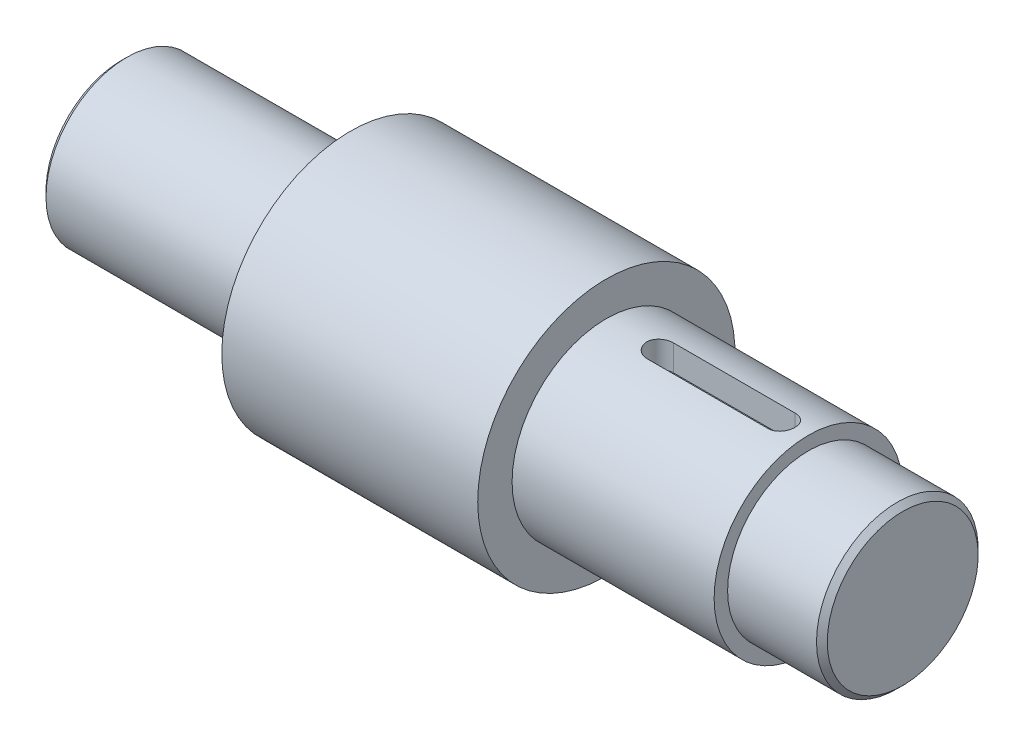
SolidWorks part; units mm, degrees
ref_plane "Alzado" through (0, 0, 0) normal (0, 0, 1) x (1, 0, 0)
ref_plane "Planta" through (0, 0, 0) normal (0, 1, 0) x (1, 0, 0)
ref_plane "Vista lateral" through (0, 0, 0) normal (1, 0, 0) x (0, 0, -1)
sketch "Croquis1" plane through (0, 0, 0) normal (0, 0, 1) x (1, 0, 0)
  line L0 (0, 0) -> (290, 0)
  line L1 (290, 0) -> (290, 30)
  line L2 (290, 30) -> (255, 30)
  line L5 (85, 47.75) -> (85, 30)
  line L6 (85, 30) -> (0, 30)
  line L7 (0, 30) -> (0, 0)
  line L8 (85, 47.75) -> (180, 47.75)
  line L10 (180, 47.75) -> (180, 35)
  line L11 (180, 35) -> (255, 35)
  line L12 (255, 35) -> (255, 30)
  dimension "D1" = 30
  dimension "D2" = 30
  dimension "D3" = 47.75
  dimension "D4" = 35
  dimension "D5" = 95
  dimension "D6" = 290
  dimension "D7" = 75
  dimension "D8" = 35
revolve "Revolución1" add sketch "Croquis1" angle 360 about L0
chamfer "Chaflán1" distance 2 angle 45 2 edges at (290, 0, 30) (0, 0, 30)
ref_plane "Plano1" through (0, 35, 0) normal (0, 1, 0) x (1, 0, 0)
sketch "Croquis2" plane through (30.6858, 35, 0) normal (0, 1, 0) x (1, 0, 0)
  line L3 (169.3142, -5) -> (214.3142, -5)
  line L7 (169.3142, 5) -> (214.3142, 5)
  line L8 (169.3142, 0) -> (214.3142, 0) construction
  arc A2 (169.3142, -5) -> (169.3142, 5) centre (169.3142, 0) cw
  arc A3 (214.3142, -5) -> (214.3142, 5) centre (214.3142, 0) ccw
  dimension "D1" = 5
  dimension "D2" = 5
extrude "Cortar-Extruir1" cut sketch "Croquis2" against normal blind 10 contours A3 L7 A2 L3
